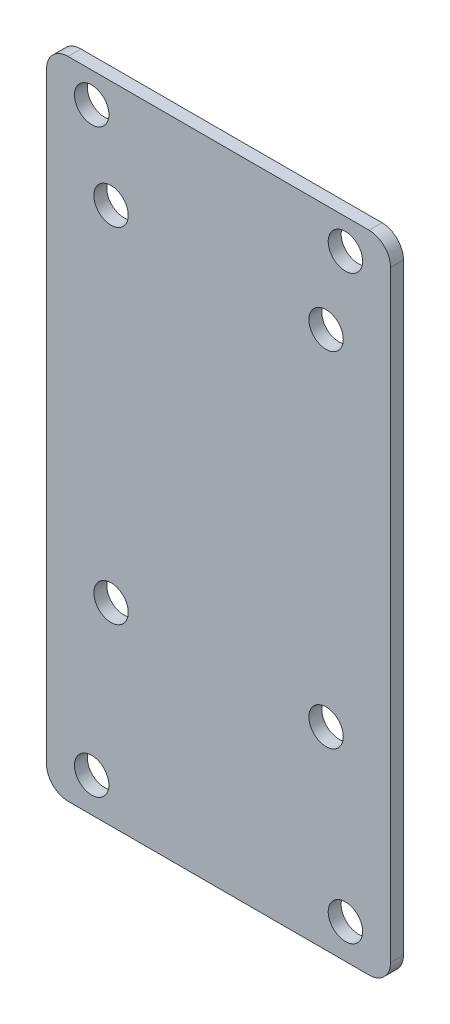
SolidWorks part; units mm, degrees
ref_plane "Front" through (0, 0, 0) normal (0, 0, 1) x (1, 0, 0)
ref_plane "Top" through (0, 0, 0) normal (0, 1, 0) x (1, 0, 0)
ref_plane "Right" through (0, 0, 0) normal (1, 0, 0) x (0, 0, -1)
sketch "Sketch1" plane through (0, 0, 0) normal (0, 0, 1) x (1, 0, 0)
  line L1 (-40, 75) -> (40, 75)
  line L2 (-40, 75) -> (-40, -75)
  line L3 (-40, -75) -> (40, -75)
  line L4 (40, 75) -> (40, -75)
  line L5 (-40, 75) -> (40, -75) construction
  line L6 (-40, -75) -> (40, 75) construction
  circle A0 centre (-29.5, 68) radius 4
  circle A1 centre (29.5, 68) radius 4
  circle A2 centre (29.5, -67) radius 4
  circle A3 centre (-29.5, -67) radius 4
  circle A4 centre (-25, 50) radius 4
  circle A5 centre (25, 50) radius 4
  circle A6 centre (25, -30) radius 4
  circle A7 centre (-25, -30) radius 4
  point P0 (0, 0)
  dimension "D8" = 8
  dimension "D9" = 8
  dimension "D10" = 8
  dimension "D11" = 8
  dimension "D15" = 8
  dimension "D16" = 8
  dimension "D17" = 8
  dimension "D18" = 8
  dimension "D1" = 80
  dimension "D2" = 150
  dimension "D3" = 59
  dimension "D4" = 59
  dimension "D5" = 0
  dimension "D6" = 29.5
  dimension "D7" = 7
  dimension "D12" = 135
  dimension "D13" = 0
  dimension "D14" = 29.5
  dimension "D19" = 25
  dimension "D20" = 50
  dimension "D21" = 25
  dimension "D22" = 25
  dimension "D23" = 25
  dimension "D24" = 45
  dimension "D25" = 45
  dimension "D26" = 50
extrude "Boss-Extrude1" add sketch "Sketch1" along normal blind 3
sketch "Sketch4" plane through (0, 0, 0) normal (1, 0, 0) x (0, 0, -1)
  line L0 (0, 0) -> (-36.5673, 0) construction
fillet "Fillet3" radius 5 4 edges at (-40, 75, 1.5) (40, 75, 1.5) (-40, -75, 1.5) (40, -75, 1.5)
